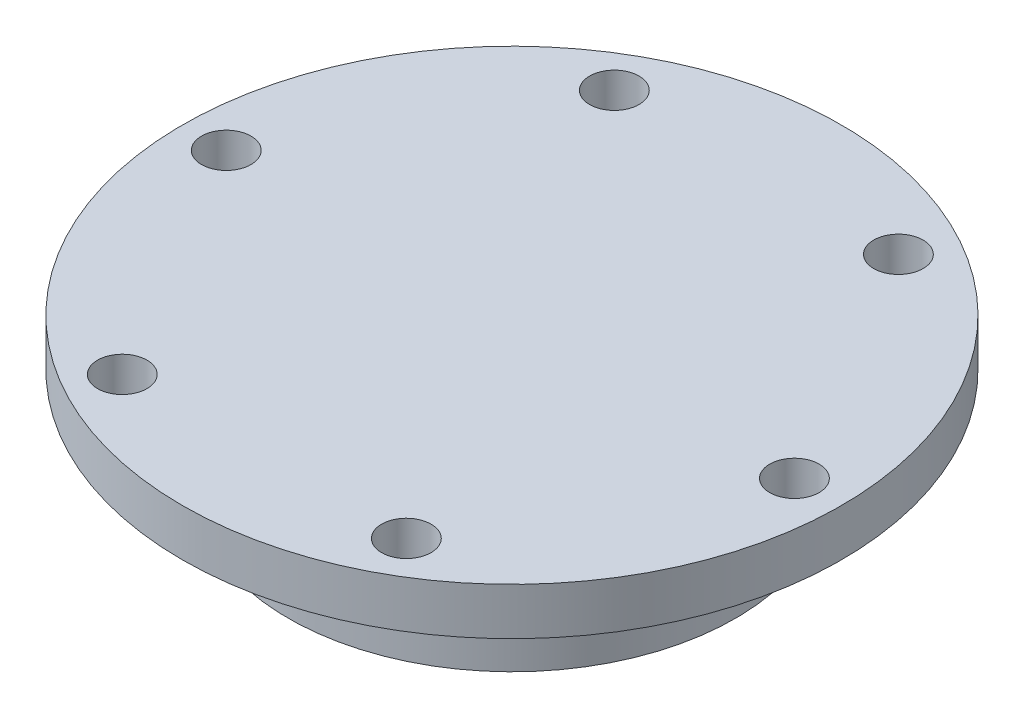
SolidWorks part; units mm, degrees
ref_plane "Alzado" through (0, 0, 0) normal (0, 0, 1) x (1, 0, 0)
ref_plane "Planta" through (0, 0, 0) normal (0, 1, 0) x (1, 0, 0)
ref_plane "Vista lateral" through (0, 0, 0) normal (1, 0, 0) x (0, 0, -1)
sketch "Croquis1" plane through (0, 0, 0) normal (0, 1, 0) x (1, 0, 0)
  circle A0 centre (0, 0) radius 70
  dimension "D1" = 140
extrude "Saliente-Extruir1" add sketch "Croquis1" along normal blind 10
sketch "Croquis2" plane through (0, 10, 0) normal (0, 1, 0) x (1, 0, 0)
  circle A0 centre (0, 0) radius 60
  dimension "D1" = 120
sketch "Croquis4" plane through (0, 0, 0) normal (0, -1, 0) x (-1, 0, 0)
  circle A1 centre (0, 0) radius 47.5
  dimension "D1" = 95
extrude "Saliente-Extruir2" add sketch "Croquis4" along normal blind 22
sketch "Croquis5" plane through (0, 10, 0) normal (0, 1, 0) x (1, 0, 0)
  line L0 (0, 0) -> (60, 0)
  circle A0 centre (0, 0) radius 60 construction
hole_wizard "Taladro roscado M12x1.51" positions "Croquis3D1" profile "Croquis6" tap size "M12x1.5" standard "Ansi Metric"
sketch3d "Croquis3D1"
  line L0 (0, 10, 0) -> (60, 10, 0) construction
  circle A0 centre (0, 10, 0) radius 60 construction
  point P0 (60, 10, 0)
  point P4 (0, 70, 0)
sketch "Croquis6" plane through (60, 10, 0) normal (1, 0, 0) x (0, 0, 1)
  line L0 (0, 0) -> (0, 34.6545)
  line L1 (0, 34.6545) -> (5.25, 31.5)
  line L2 (5.25, 31.5) -> (5.25, 0)
  line L5 (5.25, 0) -> (0, 0)
  line L10 (0, 34.6545) -> (-5.25, 31.5) construction
  line L11 (0, -6.35) -> (0, 107.95) construction
  dimension "Diámetro de perforador para roscar" = 10.5
  dimension "Profundidad de perforador para roscar" = 31.5
  dimension "Ángulo de perforador" = 118
pattern_circular "MatrizC1" count 6 over 360 about axis through (-0.3394, 0, 0) along (0, 1, 0) of "Taladro roscado M12x1.51"
